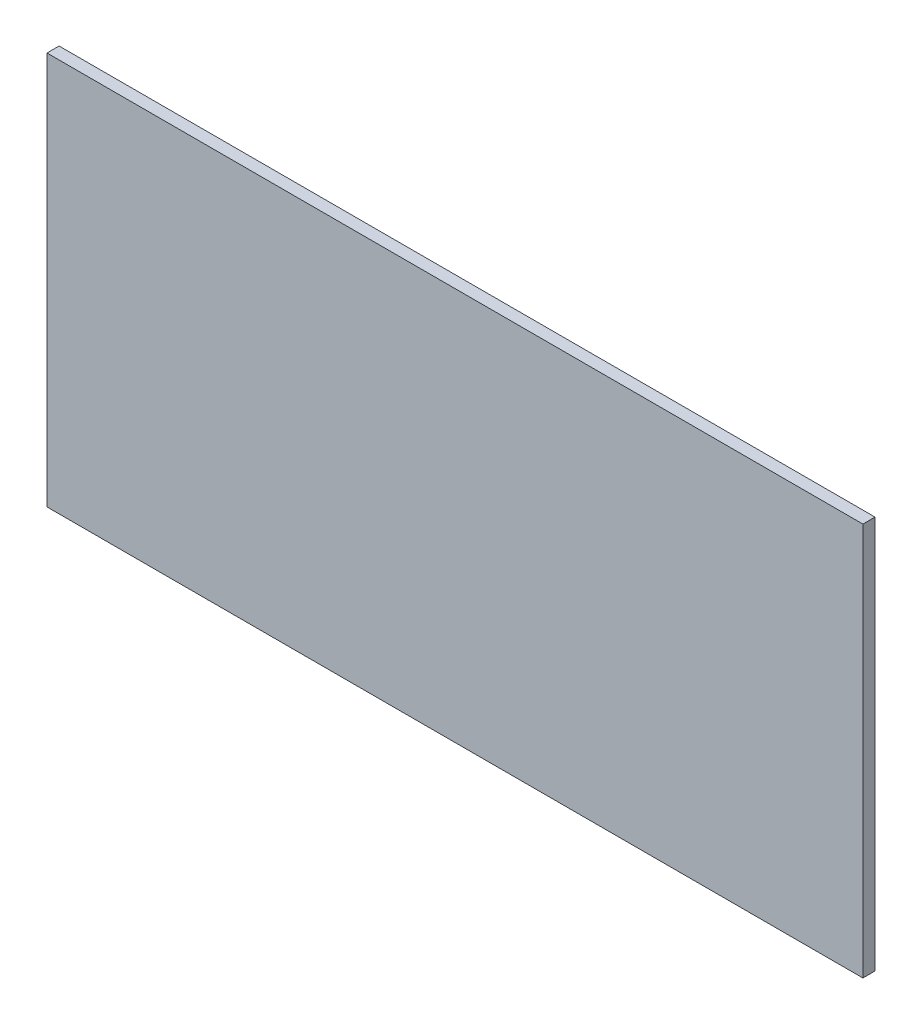
SolidWorks part; units mm, degrees
material "6061-T6 (SS)"
ref_plane "Alzado" through (0, 0, 0) normal (0, 0, 1) x (1, 0, 0)
ref_plane "Planta" through (0, 0, 0) normal (0, 1, 0) x (1, 0, 0)
ref_plane "Vista lateral" through (0, 0, 0) normal (1, 0, 0) x (0, 0, -1)
sketch "Sketch1" plane through (0, 0, 0) normal (0, 0, 1) x (1, 0, 0)
  line L1 (-101, 48.665) -> (101, 48.665)
  line L2 (-101, 48.665) -> (-101, -48.665)
  line L3 (-101, -48.665) -> (101, -48.665)
  line L4 (101, 48.665) -> (101, -48.665)
  line L5 (-101, 48.665) -> (101, -48.665) construction
  line L6 (-101, -48.665) -> (101, 48.665) construction
  point P0 (0, 0)
  dimension "D1" = 202
  dimension "D2" = 97.33
extrude "Boss-Extrude1" add sketch "Sketch1" along normal blind 3
